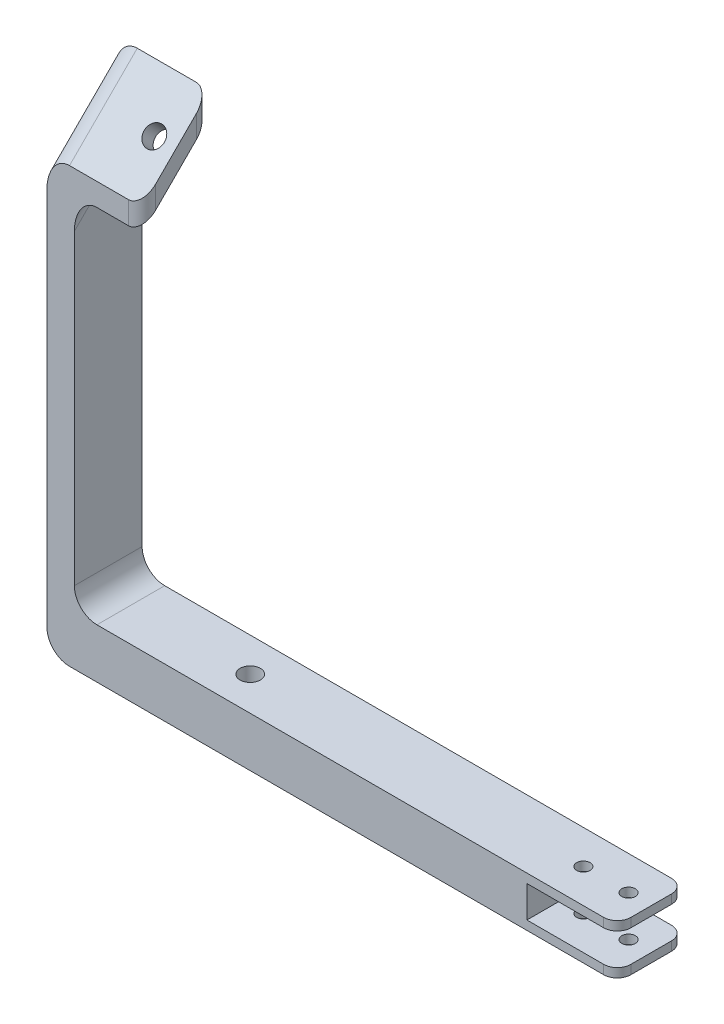
SolidWorks part; units mm, degrees
ref_plane "Alzado" through (0, 0, 0) normal (0, 0, 1) x (1, 0, 0)
ref_plane "Planta" through (0, 0, 0) normal (0, 1, 0) x (1, 0, 0)
ref_plane "Vista lateral" through (0, 0, 0) normal (1, 0, 0) x (0, 0, -1)
sketch "Croquis1" plane through (0, 0, 0) normal (0, 0, 1) x (1, 0, 0)
  line L0 (0, -3.5) -> (0, 3.5)
  line L1 (0, 3.5) -> (20, 3.5)
  line L2 (20, 3.5) -> (20, 5.5)
  line L3 (20, 5.5) -> (-100.18, 5.5)
  line L4 (-100.18, 5.5) -> (-100.18, 85.5)
  line L9 (-100.18, 85.5) -> (-85.18, 85.5)
  line L10 (-85.18, 85.5) -> (-85.18, 105.5)
  line L11 (-85.18, 105.5) -> (-106.25, 105.5)
  line L12 (-106.25, 105.5) -> (-106.25, -5.5)
  line L13 (-106.25, -5.5) -> (20, -5.5)
  line L14 (20, -5.5) -> (20, -3.5)
  line L15 (20, -3.5) -> (0, -3.5)
  dimension "D1" = 3.5
  dimension "D2" = 7
  dimension "D3" = 2
  dimension "D4" = 2
  dimension "D5" = 20
  dimension "D6" = 126.25
  dimension "D7" = 100.18
  dimension "D8" = 15
  dimension "D9" = 20
  dimension "D10" = 80
extrude "Saliente-Extruir1" add sketch "Croquis1" along normal mid plane 15
sketch "Croquis2" plane through (0, 5.5, 0) normal (0, 1, 0) x (1, 0, 0)
  circle A0 centre (15, 0) radius 1.5
  circle A1 centre (5, 0) radius 1.5
  dimension "D2" = 3
  dimension "D3" = 3
  dimension "D1" = 5
  dimension "D4" = 10
extrude "Cortar-Extruir1" cut sketch "Croquis2" against normal through all
fillet "Redondeo1" radius 3 4 edges at (20, -4.5, 7.5) (20, -4.5, -7.5) (20, 4.5, 7.5) (20, 4.5, -7.5)
fillet "Redondeo2" radius 3 2 edges at (-85.18, 95.5, -7.5) (-85.18, 95.5, 7.5)
sketch "Croquis4" plane through (-100.18, 0, 0) normal (1, 0, 0) x (0, 0, -1)
  line L0 (-7.5, 90.5) -> (7.5, 105.5)
  line L1 (-7.5, 85.5) -> (-7.5, 105.5) construction
  line L2 (7.5, 105.5) -> (7.5, 85.5) construction
  line L4 (7.5, 105.5) -> (-7.5, 105.5)
  line L5 (-7.5, 105.5) -> (-7.5, 90.5)
  line L6 (-7.5, 85.5) -> (7.5, 85.5) construction
  line L7 (-7.5, 85.5) -> (7.5, 100.5)
  line L8 (7.5, 100.5) -> (7.5, 85.5)
  line L9 (7.5, 85.5) -> (-7.5, 85.5)
  dimension "D1" = 45
  dimension "D2" = 5
extrude "Cortar-Extruir3" cut sketch "Croquis4" along normal through all
sketch "Croquis5" plane through (0, 49, 49) normal (0, 0.7071, 0.7071) x (1, 0, 0)
  line L0 (-106.25, 58.6899) -> (-106.25, 79.9031) construction
  circle A0 centre (-89.98, 69.2965) radius 2.25
  point P6 (-106.25, 69.2965)
  dimension "D1" = 4.5
  dimension "D2" = 10.2
extrude "Cortar-Extruir4" cut sketch "Croquis5" against normal through all
sketch "Croquis6" plane through (-100.18, 0, 0) normal (1, 0, 0) x (0, 0, -1)
  line L3 (-7.5, 105.5) -> (-7.5, 90.5)
  line L4 (-7.5, 105.5) -> (-7.5, 90.5)
  line L9 (-7.5, 90.5) -> (7.5, 105.5)
  line L11 (7.5, 105.5) -> (-7.5, 105.5)
  line L13 (-7.5, 90.5) -> (7.5, 105.5)
  line L15 (7.5, 105.5) -> (-7.5, 105.5)
  dimension "D1" = 0
extrude "Cortar-Extruir5" cut sketch "Croquis6" against normal through all
sketch "Croquis7" plane through (0, 5.5, 0) normal (0, 1, 0) x (1, 0, 0)
  line L0 (-106.25, -7.5) -> (-106.25, 7.5) construction
  line L1 (-100.18, -7.5) -> (-100.18, 7.5) construction
  circle A0 centre (-68.75, 0) radius 2.25
  point P4 (-106.25, 0)
  point P9 (-100.18, 0)
  dimension "D1" = 4.5
  dimension "D2" = 37.5
extrude "Cortar-Extruir6" cut sketch "Croquis7" against normal blind 7
fillet "Redondeo3" radius 5 4 edges at (-100.18, 5.5, 0) (-106.25, -5.5, 0) (-106.25, 98, 0) (-100.18, 93, 0)
